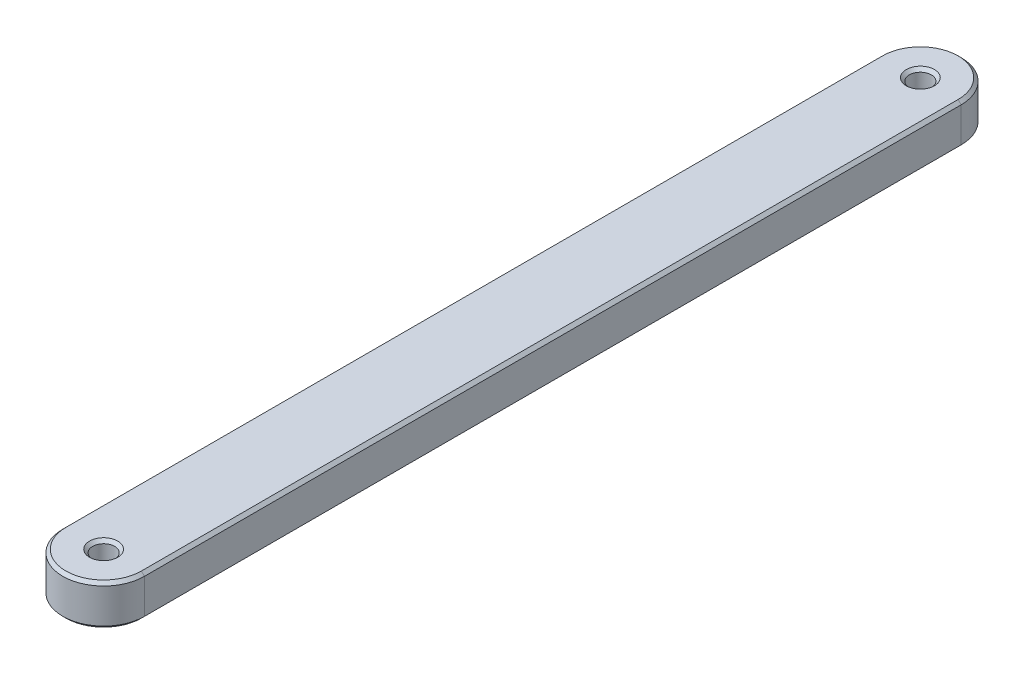
SolidWorks part; units mm, degrees
ref_plane "Front Plane" through (0, 0, 0) normal (0, 0, 1) x (1, 0, 0)
ref_plane "Top Plane" through (0, 0, 0) normal (0, 1, 0) x (1, 0, 0)
ref_plane "Right Plane" through (0, 0, 0) normal (1, 0, 0) x (0, 0, -1)
sketch "Sketch1" plane through (0, 0, 0) normal (0, 1, 0) x (1, 0, 0)
  line L0 (-10, 100) -> (10, 100) construction
  line L2 (10, -100) -> (10, 100)
  line L4 (-10, -100) -> (-10, 100)
  line L5 (10, -100) -> (-10, 100) construction
  line L6 (10, 100) -> (-10, -100) construction
  line L15 (-10, 0) -> (10, 0) construction
  circle A4 centre (0, -100) radius 2.7
  circle A9 centre (0, 100) radius 2.7
  arc A10 (10, -100) -> (-10, -100) centre (0, -100) cw
  arc A11 (10, 100) -> (-10, 100) centre (0, 100) ccw
  point P0 (0, 0)
  dimension "D3" = 5.4
  dimension "D1" = 200
  dimension "D2" = 20
extrude "Boss-Extrude1" add sketch "Sketch1" along normal blind 10
sketch "Sketch2" plane through (0, 0, 0) normal (0, -1, 0) x (1, 0, 0)
  circle A0 centre (0, 100) radius 6.5
  circle A1 centre (0, -100) radius 6.5
  dimension "D1" = 13
extrude "Cut-Extrude1" cut sketch "Sketch2" against normal blind 4
chamfer "Chamfer1" distance 0.75 angle 45 14 edges at (0, 10, -97.3) (0, 10, 102.7) (-10, 10, 0) (0, 10, 110) (0, 10, -110) (10, 10, 0) (-10, 0, 0) (0, 0, 110) (0, 0, -110) (10, 0, 0) (0, 4, -102.7) (0, 4, 97.3) (0, 0, 93.5) (0, 0, -106.5)
